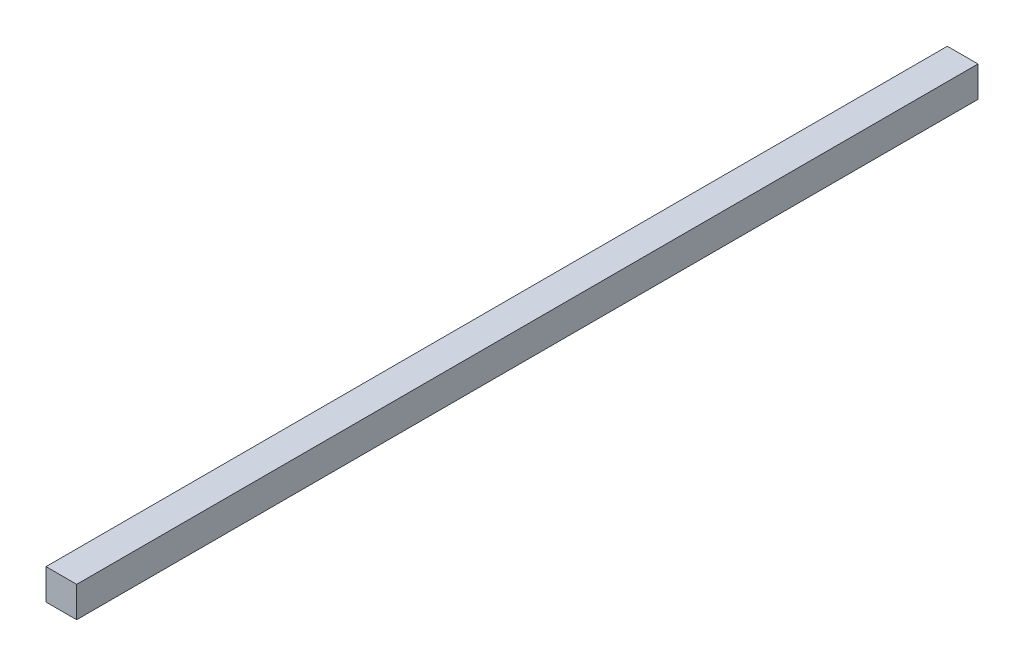
SolidWorks part; units mm, degrees
ref_plane "Front Plane" through (0, 0, 0) normal (0, 0, 1) x (1, 0, 0)
ref_plane "Top Plane" through (0, 0, 0) normal (0, 1, 0) x (1, 0, 0)
ref_plane "Right Plane" through (0, 0, 0) normal (1, 0, 0) x (0, 0, -1)
sketch "Sketch1" plane through (0, 0, 0) normal (1, 0, 0) x (0, 0, -1)
  line L0 (0, 0) -> (41.4909, 0)
  line L1 (41.4909, 0) -> (41.4909, 1.4122)
  line L2 (41.4909, 1.4122) -> (0, 1.4122)
  line L3 (0, 1.4122) -> (0, 0)
extrude "Boss-Extrude2" add sketch "Sketch1" along normal blind 1.4122
